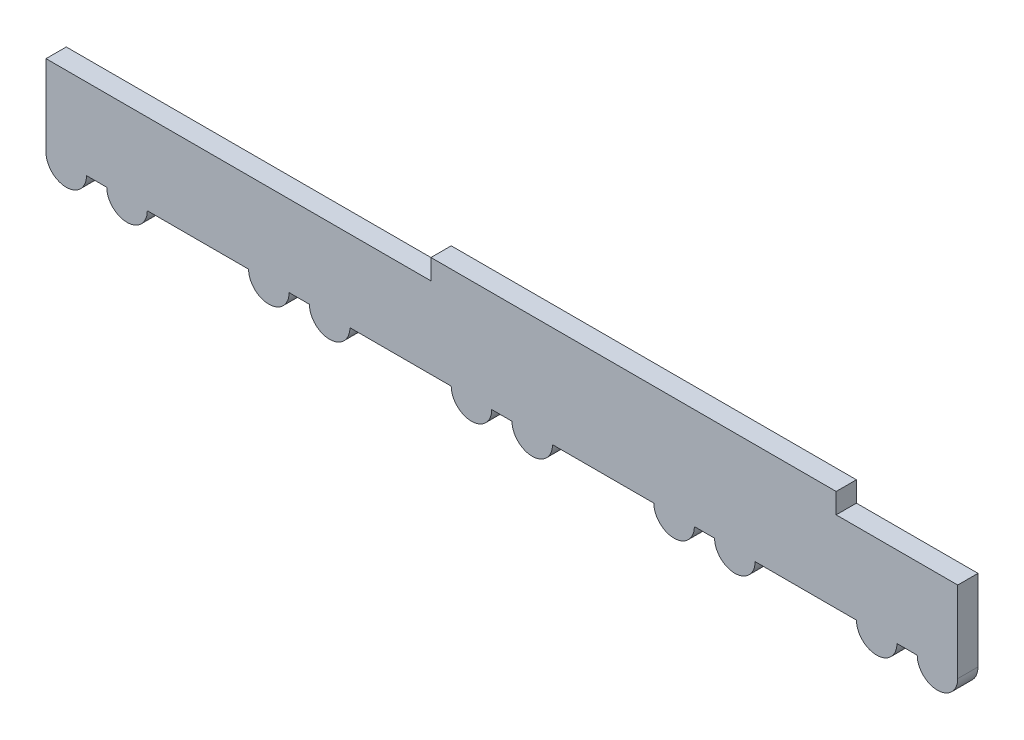
SolidWorks part; units mm, degrees
material "Perspex (TM) GS Acrylic Cast Sheet"
ref_plane "Ebene vorne" through (0, 0, 0) normal (0, 0, 1) x (1, 0, 0)
ref_plane "Ebene oben" through (0, 0, 0) normal (0, 1, 0) x (1, 0, 0)
ref_plane "Ebene rechts" through (0, 0, 0) normal (1, 0, 0) x (0, 0, -1)
sketch "Skizze1" plane through (0, 0, 0) normal (0, 0, 1) x (1, 0, 0)
  line L0 (-102.5, -10) -> (-97.5, -10)
  line L1 (112.5, -10) -> (-112.5, -10) construction
  line L2 (112.5, -10) -> (112.5, 10)
  line L3 (112.5, 10) -> (-112.5, 10)
  line L4 (-112.5, -10) -> (-112.5, 10)
  line L5 (112.5, -10) -> (-112.5, 10) construction
  line L6 (112.5, 10) -> (-112.5, -10) construction
  line L7 (-87.5, -10) -> (-52.5, -10)
  line L8 (-52.5, -10) -> (-47.5, -10)
  line L9 (-2.5, -10) -> (2.5, -10)
  line L10 (47.5, -10) -> (52.5, -10)
  line L11 (97.5, -10) -> (102.5, -10)
  line L12 (-37.5, -10) -> (-12.5, -10)
  line L13 (12.5, -10) -> (37.5, -10)
  line L14 (62.5, -10) -> (87.5, -10)
  line L16 (82.5, 10) -> (-17.5, 10)
  line L17 (82.5, 10) -> (82.5, 15)
  line L18 (82.5, 15) -> (-17.5, 15)
  line L19 (-17.5, 10) -> (-17.5, 15)
  line L20 (82.5, 10) -> (-17.5, 15) construction
  line L21 (82.5, 15) -> (-17.5, 10) construction
  arc A0 (-112.5, -10) -> (-102.5, -10) centre (-107.5, -10) ccw
  arc A1 (-97.5, -10) -> (-87.5, -10) centre (-92.5, -10) ccw
  arc A2 (-62.5, -10) -> (-52.5, -10) centre (-57.5, -10) ccw
  arc A3 (-47.5, -10) -> (-37.5, -10) centre (-42.5, -10) ccw
  arc A4 (-12.5, -10) -> (-2.5, -10) centre (-7.5, -10) ccw
  arc A5 (2.5, -10) -> (12.5, -10) centre (7.5, -10) ccw
  arc A6 (37.5, -10) -> (47.5, -10) centre (42.5, -10) ccw
  arc A7 (52.5, -10) -> (62.5, -10) centre (57.5, -10) ccw
  arc A8 (87.5, -10) -> (97.5, -10) centre (92.5, -10) ccw
  arc A9 (102.5, -10) -> (112.5, -10) centre (107.5, -10) ccw
  point P0 (0, 0)
  point P39 (32.5, 12.5)
  dimension "D3" = 5
  dimension "D5" = 5
  dimension "D1" = 225
  dimension "D2" = 20
  dimension "D4" = 5
  dimension "D6" = 35
  dimension "D8" = 95
  dimension "D9" = 100
  dimension "D10" = 5
  dimension "D7" = 5
extrude "Aufsatz-Linear austragen1" add sketch "Skizze1" along normal blind 5 contours L11 A9 L2 L3 L4 A0 L0 A1 L7 L8 A3 L12 A4 L9 A5 L13 A6 L10 A7 L14 A8 | L19 L3 L17 L18 | L7 A2
